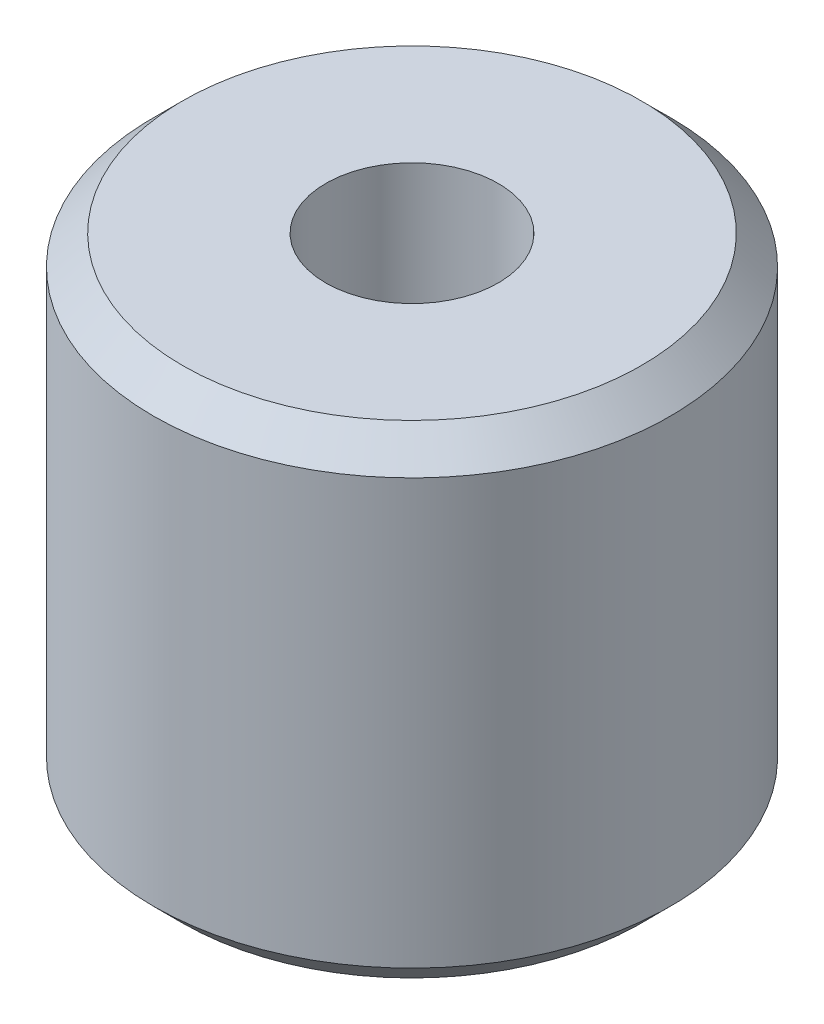
SolidWorks part; units mm, degrees
ref_plane "Front Plane" through (0, 0, 0) normal (0, 0, 1) x (1, 0, 0)
ref_plane "Top Plane" through (0, 0, 0) normal (0, 1, 0) x (1, 0, 0)
ref_plane "Right Plane" through (0, 0, 0) normal (1, 0, 0) x (0, 0, -1)
sketch "Sketch1" plane through (0, 0, 0) normal (1, 0, 0) x (0, 0, -1)
  line L0 (-11.6758, 0) -> (15.2816, 0) construction
  line L5 (0, 16.3835) -> (0, 0) construction
  line L6 (0, 4.45) -> (4.2276, 4.45)
  line L7 (4.2276, 4.45) -> (4.765, 3.9126)
  line L8 (4.765, 3.9126) -> (0, 3.9126)
  line L9 (0, 3.9126) -> (0, 4.45)
  line L10 (4.765, 3.9126) -> (4.765, 0)
  line L11 (0, 3.9126) -> (0, 0)
  line L13 (0, -3.9126) -> (0, -4.45)
  line L14 (4.2276, -4.45) -> (4.765, -3.9126)
  line L15 (4.765, -3.9126) -> (0, -3.9126)
  line L16 (0, -4.45) -> (4.2276, -4.45)
  line L17 (0, 0.1591) -> (0, -3.9126)
  line L18 (4.765, -3.9126) -> (4.765, 0)
  dimension "D1" = 45
  dimension "D2" = 0.76
  dimension "D3" = 9.53
  dimension "D4" = 8.9
revolve "Revolve1" add sketch "Sketch1" angle 360 about L5
sketch "Sketch2" plane through (0, 4.45, 0) normal (0, 1, 0) x (1, 0, 0)
  circle A0 centre (0, 0) radius 1.59
  point P3 (0, 0)
  dimension "D1" = 3.18
extrude "Cut-Extrude1" cut sketch "Sketch2" against normal through all
